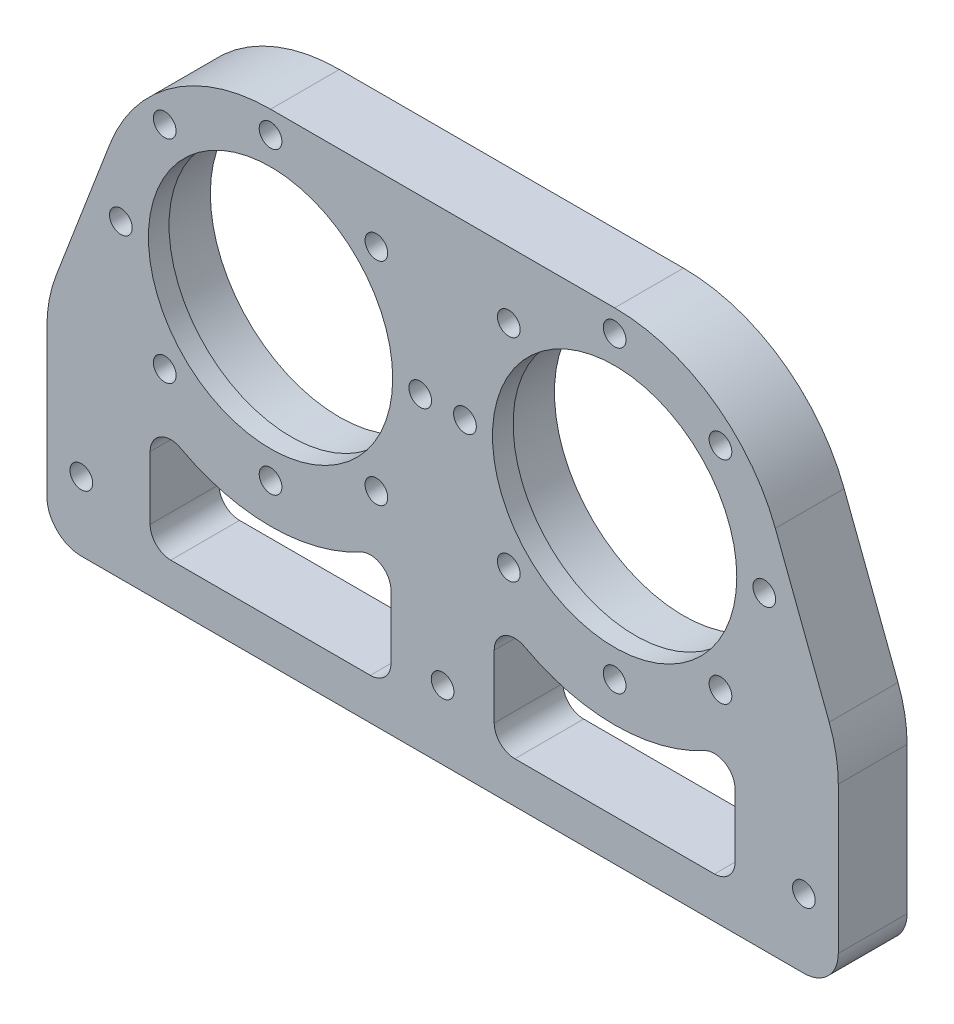
SolidWorks part; units mm, degrees
material "5052-H34"
ref_plane "正面" through (0, 0, 0) normal (0, 0, 1) x (1, 0, 0)
ref_plane "平面" through (0, 0, 0) normal (0, 1, 0) x (1, 0, 0)
ref_plane "右側面" through (0, 0, 0) normal (1, 0, 0) x (0, 0, -1)
sketch "ｽｹｯﾁ1" plane through (0, 0, 0) normal (0, 0, 1) x (1, 0, 0)
  line L0 (-57.5, 15) -> (-2.5, 15) construction
  line L1 (57.5, 15) -> (-57.5, 15)
  line L2 (57.5, 15) -> (57.5, -15)
  line L3 (57.5, -15) -> (-57.5, -15)
  line L4 (-57.5, 15) -> (-57.5, -15)
  line L5 (57.5, 15) -> (-57.5, -15) construction
  line L6 (57.5, -15) -> (-57.5, 15) construction
  line L7 (0, 15) -> (0, -15) construction
  line L8 (-57.5, 0) -> (57.5, 0) construction
  line L9 (-25, -15) -> (-25, 30) construction
  line L10 (-48.3514, 38.9281) -> (-57.5, 15)
  line L11 (-25, 55) -> (25, 55)
  line L12 (48.3514, 38.9281) -> (57.5, 15)
  circle A0 centre (-25, 30) radius 25
  circle A1 centre (25, 30) radius 25
  point P0 (0, 0)
  point P11 (2.5, 15)
  dimension "D4" = 50
  dimension "D6" = 50
  dimension "D1" = 115
  dimension "D2" = 30
  dimension "D3" = 55
  dimension "D5" = 45
extrude "ﾎﾞｽ - 押し出し1" add sketch "ｽｹｯﾁ1" along normal blind 10 contours L1 A1 A0 L4 L3 L2 | A0 L1 | L1 A1 L11 A0 | A1 L1 | A1 L1 | L1 A0 | L12 A1 L1 | A0 L10 L1 | L1 A1 A0
fillet "ﾌｨﾚｯﾄ1" radius 20 2 edges at (-57.5, 15, 5) (57.5, 15, 5)
sketch "ｽｹｯﾁ2" plane through (0, 0, 10) normal (0, 0, 1) x (1, 0, 0)
  line L0 (0, 0) -> (0, 55) construction
  line L1 (-25, 55) -> (25, 55) construction
  line L2 (25, 30) -> (25, -15) construction
  line L3 (57.5, -15) -> (-57.5, -15) construction
  circle A0 centre (25, 30) radius 18.75
  circle A1 centre (-25, 30) radius 18.75
  dimension "D1" = 37.5
extrude "ｶｯﾄ - 押し出し1" cut sketch "ｽｹｯﾁ2" against normal through all
sketch "ｽｹｯﾁ5" plane through (0, 0, 0) normal (0, 0, -1) x (-1, 0, 0)
  line L0 (0, 0) -> (0, 55) construction
  line L1 (25, 55) -> (-25, 55) construction
  line L2 (-25, 48.75) -> (-25, 11.25) construction
  circle A0 centre (-25, 30) radius 21.75 construction
  circle A1 centre (-25, 51.75) radius 1.65
  circle A2 centre (-9.6204, 45.3796) radius 1.65
  circle A3 centre (-3.25, 30) radius 1.65
  circle A4 centre (-9.6204, 14.6204) radius 1.65
  circle A5 centre (-25, 8.25) radius 1.65
  circle A6 centre (-40.3796, 14.6204) radius 1.65
  circle A7 centre (-46.75, 30) radius 1.65
  circle A8 centre (-40.3796, 45.3796) radius 1.65
  circle A9 centre (25, 30) radius 21.75 construction
  circle A10 centre (40.3796, 45.3796) radius 1.65
  circle A11 centre (46.75, 30) radius 1.65
  circle A12 centre (40.3796, 14.6204) radius 1.65
  circle A13 centre (25, 8.25) radius 1.65
  circle A14 centre (9.6204, 14.6204) radius 1.65
  circle A15 centre (3.25, 30) radius 1.65
  circle A16 centre (9.6204, 45.3796) radius 1.65
  circle A17 centre (25, 51.75) radius 1.65
  circle A18 centre (-25, 30) radius 18.75 construction
  point P22 (-25, 30)
  point P43 (25, 30)
  dimension "D1" = 43.5
  dimension "D2" = 3.3
  dimension "D3" = 8
extrude "ｶｯﾄ - 押し出し4" cut sketch "ｽｹｯﾁ5" against normal through all
sketch "ｽｹｯﾁ6" plane through (0, 0, 0) normal (0, 0, -1) x (-1, 0, 0)
  line L0 (-57.5, -15) -> (57.5, -15) construction
  line L1 (-57.5, 11.307) -> (-57.5, -15) construction
  line L2 (0, 0) -> (0, -15) construction
  circle A0 centre (-52.5, -5) radius 1.65
  circle A1 centre (52.5, -5) radius 1.65
  circle A2 centre (0, -5) radius 1.65
  dimension "D1" = 3.3
  dimension "D2" = 10
  dimension "D3" = 5
  dimension "D4" = 10
  dimension "D5" = 3.3
extrude "ｶｯﾄ - 押し出し5" cut sketch "ｽｹｯﾁ6" against normal through all
sketch "ｽｹｯﾁ7" plane through (0, 0, 10) normal (0, 0, 1) x (1, 0, 0)
  circle A0 centre (-25, 30) radius 18.75
  circle A1 centre (25, 30) radius 18.75
  circle A2 centre (-25, 30) radius 18.75 construction
  circle A3 centre (-25, 30) radius 17.75
  circle A4 centre (25, 30) radius 17.75
  dimension "D1" = 1
extrude "ﾎﾞｽ - 押し出し2" add sketch "ｽｹｯﾁ7" against normal blind 3
sketch "ｽｹｯﾁ8" plane through (0, 0, 0) normal (0, 0, -1) x (-1, 0, 0)
  line L0 (0, 0) -> (0, 55) construction
  line L1 (25, 55) -> (-25, 55) construction
  line L2 (-42.5, -9) -> (-7.5, -9)
  line L3 (-7.5, -9) -> (-7.5, 8.7868)
  line L4 (-42.5, -9) -> (-42.5, 8.7868)
  line L5 (-52.5, -5) -> (0, -5) construction
  line L6 (-25, -5) -> (-25, 30) construction
  line L7 (-57.5, -15) -> (57.5, -15) construction
  line L8 (42.5, -9) -> (42.5, 8.7868)
  line L9 (42.5, -9) -> (7.5, -9)
  line L10 (7.5, -9) -> (7.5, 8.7868)
  arc A0 (-42.5, 8.7868) -> (-7.5, 8.7868) centre (-25, 30) ccw
  arc A1 (42.5, 8.7868) -> (7.5, 8.7868) centre (25, 30) cw
  dimension "D1" = 55
  dimension "D2" = 6
  dimension "D3" = 35
extrude "ｶｯﾄ - 押し出し6" cut sketch "ｽｹｯﾁ8" against normal up to surface (10 mm away) up to face at (50.85, -5, 10)
fillet "ﾌｨﾚｯﾄ5" radius 5 2 edges at (-57.5, -15, 5) (57.5, -15, 5)
fillet "ﾌｨﾚｯﾄ6" radius 3 8 edges at (42.5, -9, 5) (42.5, 8.7868, 5) (7.5, 8.7868, 5) (7.5, -9, 5) (-42.5, -9, 5) (-7.5, -9, 5) (-7.5, 8.7868, 5) (-42.5, 8.7868, 5)
